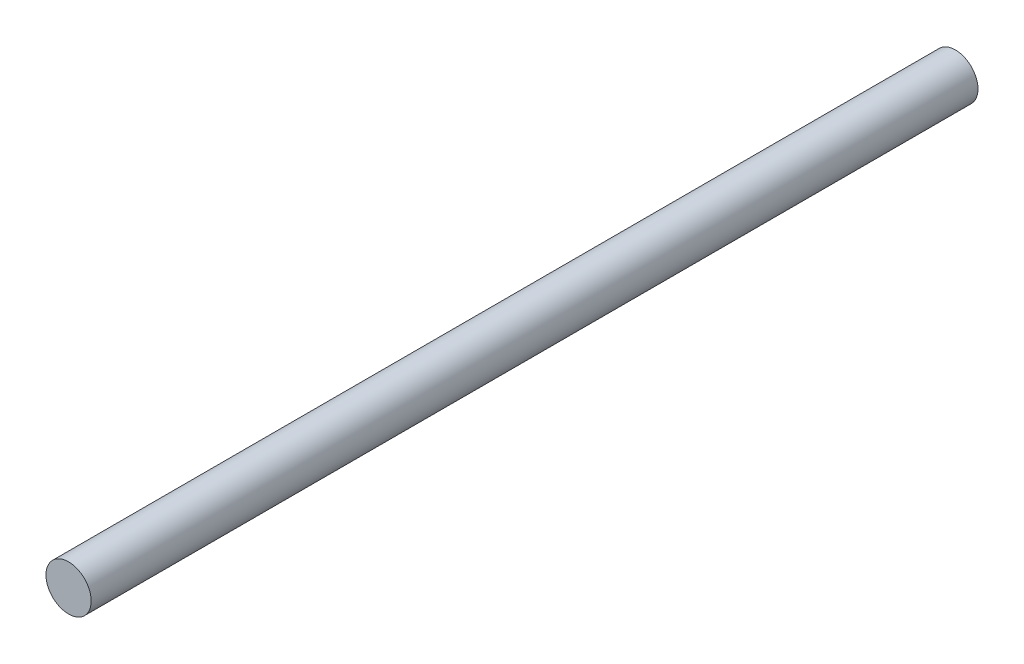
SolidWorks part; units mm, degrees
ref_plane "Front Plane" through (0, 0, 0) normal (0, 0, 1) x (1, 0, 0)
ref_plane "Top Plane" through (0, 0, 0) normal (0, 1, 0) x (1, 0, 0)
ref_plane "Right Plane" through (0, 0, 0) normal (1, 0, 0) x (0, 0, -1)
sketch "Sketch1" plane through (0, 0, 0) normal (0, 0, 1) x (1, 0, 0)
  circle A0 centre (0, 0) radius 3.175
  dimension "D1" = 6.35
extrude "Boss-Extrude1" add sketch "Sketch1" along normal blind 124.46
equation "\"rodDiameter\"= 1in / 4"
equation "\"rodLength\"= 4.9in"
equation "\"D1@Sketch1\"=\"rodDiameter\""
equation "\"D1@Boss-Extrude1\"=\"rodLength\""
